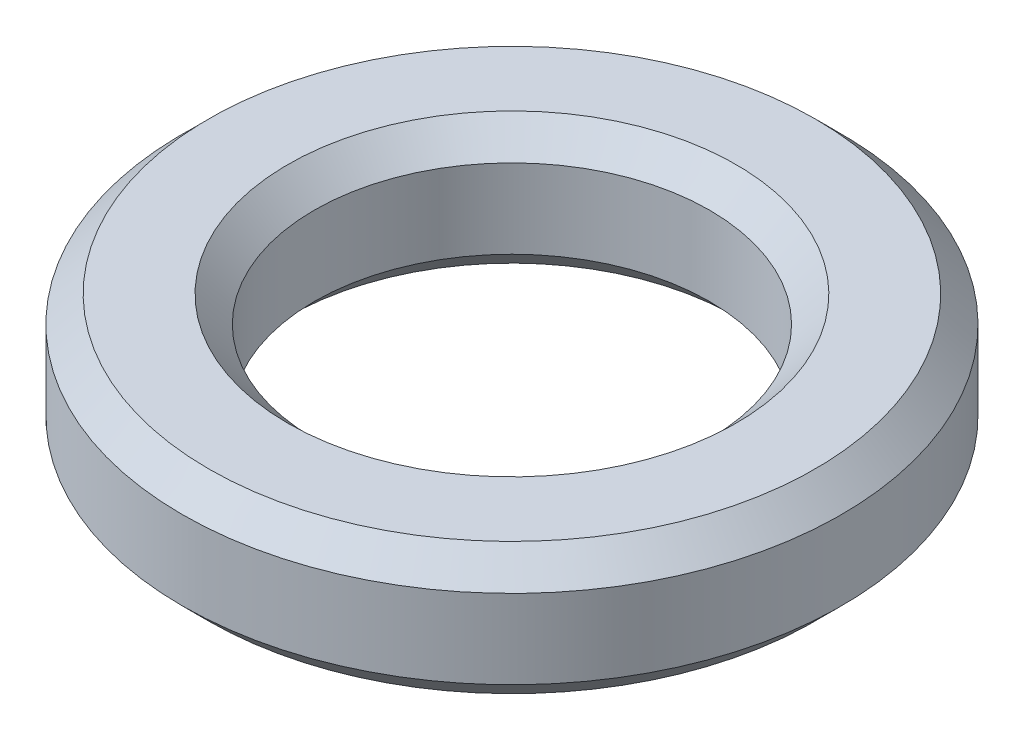
SolidWorks part; units mm, degrees
ref_plane "Front Plane" through (0, 0, 0) normal (0, 0, 1) x (1, 0, 0)
ref_plane "Top Plane" through (0, 0, 0) normal (0, 1, 0) x (1, 0, 0)
ref_plane "Right Plane" through (0, 0, 0) normal (1, 0, 0) x (0, 0, -1)
sketch "Sketch1" plane through (0, 0, 0) normal (0, 0, 1) x (1, 0, 0)
  line L0 (0, 24.0064) -> (0, -13.4936) construction
  line L1 (7.5, 1.9808) -> (8.5, 2.9808)
  line L2 (11.5, -2.0192) -> (8.5, -2.0192)
  line L3 (12.5, -1.0192) -> (12.5, 1.9808)
  line L4 (11.5, 2.9808) -> (8.5, 2.9808)
  line L5 (7.5, -1.0192) -> (7.5, 1.9808)
  line L6 (12, -1.5192) -> (8, 2.4808) construction
  line L7 (12, 2.4808) -> (8, -1.5192) construction
  line L8 (5.1353, 0.4808) -> (14.1875, 0.4808) construction
  line L9 (10, -3.2388) -> (10, 4.8731) construction
  line L10 (12.5, 1.9808) -> (11.5, 2.9808)
  line L11 (7.5, -1.0192) -> (8.5, -2.0192)
  line L12 (12.5, -1.0192) -> (11.5, -2.0192)
  point P3 (10, 0.4808)
  dimension "D3" = 10
  dimension "D5" = 45
revolve "Revolve1" add sketch "Sketch1" angle 360 about L0
